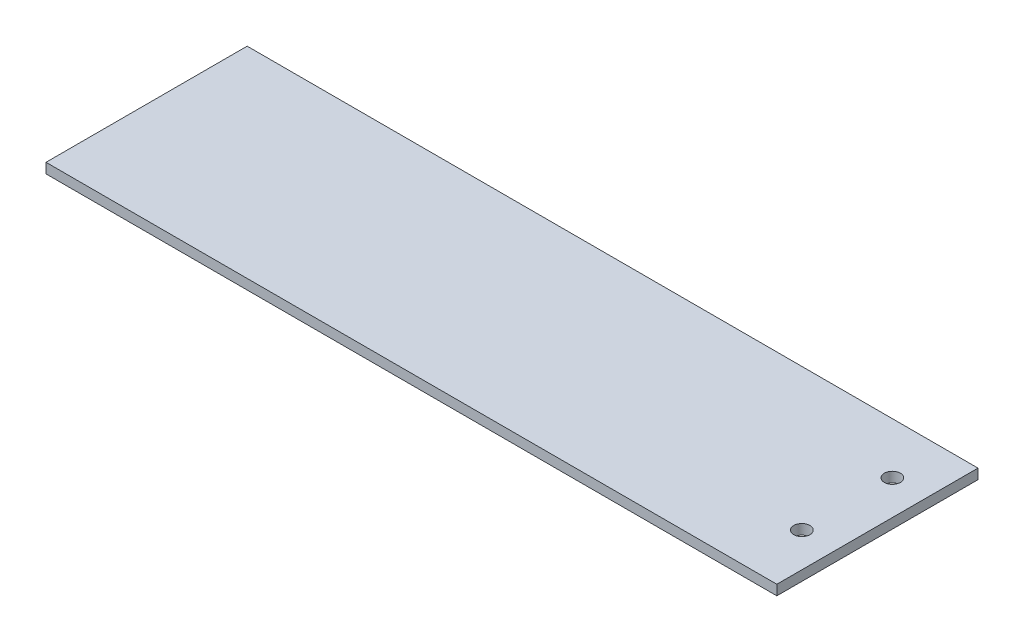
SolidWorks part; units mm, degrees
material "Liga 1060"
ref_plane "Front" through (0, 0, 0) normal (0, 0, 1) x (1, 0, 0)
ref_plane "Top" through (0, 0, 0) normal (0, 1, 0) x (1, 0, 0)
ref_plane "Right" through (0, 0, 0) normal (1, 0, 0) x (0, 0, -1)
sketch "Esboço1" plane through (0, 0, 0) normal (0, 1, 0) x (1, 0, 0)
  line L0 (-343.1603, 35.3549) -> (-343.1603, -35.4451) construction
  line L1 (-343.1603, -50) -> (20.1397, -50)
  line L2 (-343.1603, -50) -> (-343.1603, 50)
  line L3 (-343.1603, 50) -> (20.1397, 50)
  line L4 (20.1397, -50) -> (20.1397, 50)
  line L5 (20.1397, -98.1394) -> (20.1397, 97.2106) construction
  line L6 (20.1397, 0) -> (-343.1603, 0) construction
  circle A0 centre (3.0397, 24.5346) radius 4 construction
  circle A1 centre (3.0397, -20.4654) radius 4 construction
  circle A2 centre (3.0397, 24.5346) radius 4
  circle A3 centre (3.0397, -20.4654) radius 4
  point P0 (0, 0)
  dimension "D1" = 100
extrude "Ressalto-extrusão1" add sketch "Esboço1" along normal blind 5
